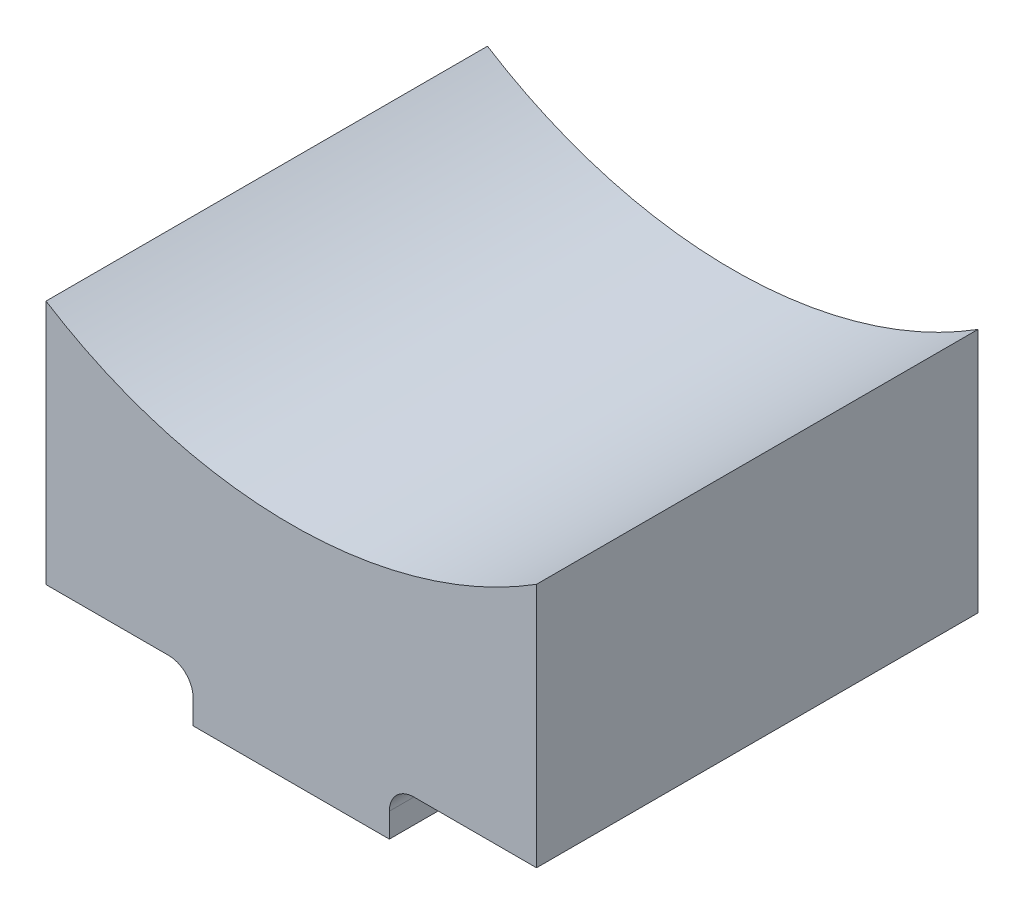
SolidWorks part; units mm, degrees
material "Ice"
ref_plane "Front Plane" through (0, 0, 0) normal (0, 0, 1) x (1, 0, 0)
ref_plane "Top Plane" through (0, 0, 0) normal (0, 1, 0) x (1, 0, 0)
ref_plane "Right Plane" through (0, 0, 0) normal (1, 0, 0) x (0, 0, -1)
sketch "Sketch1" plane through (0, 0, 0) normal (0, 0, 1) x (1, 0, 0)
  line L0 (10, 3.9928) -> (10, -6.0185)
  line L1 (-10, 3.9928) -> (-10, -6.0185)
  line L2 (-10, -6.0185) -> (-5, -6.0185)
  line L3 (10, -6.0185) -> (5, -6.0185)
  line L4 (4, -7.0185) -> (4, -8.0072)
  line L5 (0, 0) -> (0, 15264.4079) construction
  line L6 (-4, -7.0185) -> (-4, -8.0072)
  line L11 (-4, -8.0072) -> (4, -8.0072)
  arc A0 (-10, 3.9928) -> (10, 3.9928) centre (0, 19.8337) ccw
  arc A1 (4, -7.0185) -> (5, -6.0185) centre (5, -7.0185) cw
  arc A2 (-4, -7.0185) -> (-5, -6.0185) centre (-5, -7.0185) ccw
  point P13 (4, -6.0185)
  dimension "D1" = 10
  dimension "D2" = 10
  dimension "D3" = 12
extrude "Boss-Extrude1" add sketch "Sketch1" along normal mid plane 18 contours A0 L0 L3 A1 L4 L11 L6 A2 L2 L1
